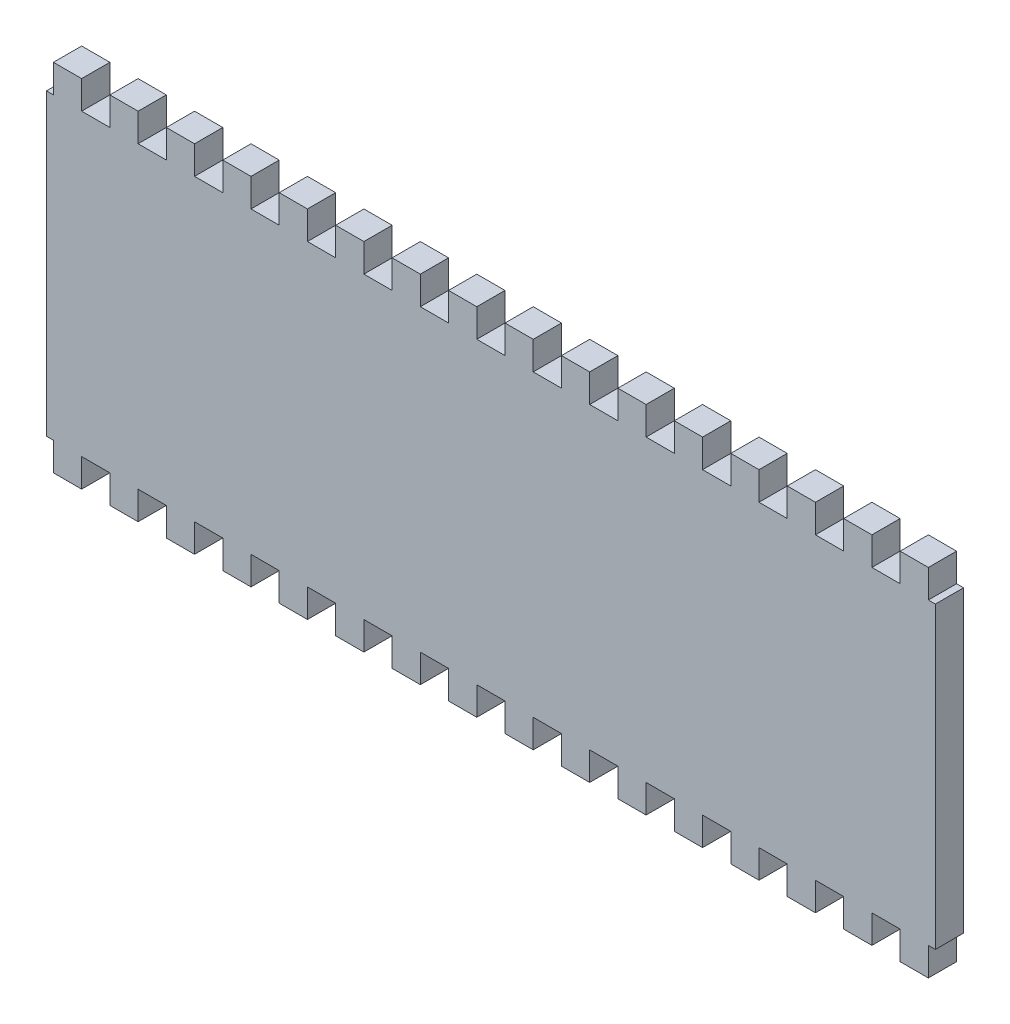
SolidWorks part; units mm, degrees
ref_plane "Front Plane" through (0, 0, 0) normal (0, 0, 1) x (1, 0, 0)
ref_plane "Top Plane" through (0, 0, 0) normal (0, 1, 0) x (1, 0, 0)
ref_plane "Right Plane" through (0, 0, 0) normal (1, 0, 0) x (0, 0, -1)
sketch "Sketch1" plane through (0, 0, 0) normal (0, 0, 1) x (1, 0, 0)
  line L1 (50, -20) -> (-50, -20)
  line L2 (50, -20) -> (50, 20)
  line L3 (50, 20) -> (-50, 20)
  line L4 (-50, -20) -> (-50, 20)
  line L5 (50, -20) -> (-50, 20) construction
  line L6 (50, 20) -> (-50, -20) construction
  point P0 (0, 0)
  dimension "D1" = 40
  dimension "D2" = 100
extrude "Boss-Extrude1" add sketch "Sketch1" along normal blind 3.175
sketch "Sketch2" plane through (0, 0, 3.175) normal (0, 0, 1) x (1, 0, 0)
  line L0 (-50, -20) -> (50, -20) construction
  line L1 (-1.5875, -16.825) -> (1.5875, -16.825)
  line L2 (-1.5875, -16.825) -> (-1.5875, -23.175)
  line L3 (-1.5875, -23.175) -> (1.5875, -23.175)
  line L4 (1.5875, -16.825) -> (1.5875, -23.175)
  line L5 (-1.5875, -16.825) -> (1.5875, -23.175) construction
  line L6 (-1.5875, -23.175) -> (1.5875, -16.825) construction
  point P0 (0, -20)
  dimension "D1" = 6.35
  dimension "D2" = 3.175
extrude "Cut-Extrude1" cut sketch "Sketch2" against normal blind 3.175
pattern_linear "LPattern1" count 10 spacing 6.35 along (1, 0, 0) count 10 spacing 6.35 along (-1, 0, 0) of "Cut-Extrude1"
mirror "Mirror1" about plane through (0, 0, 0) normal (0, 1, 0) of "LPattern1", "Cut-Extrude1"
